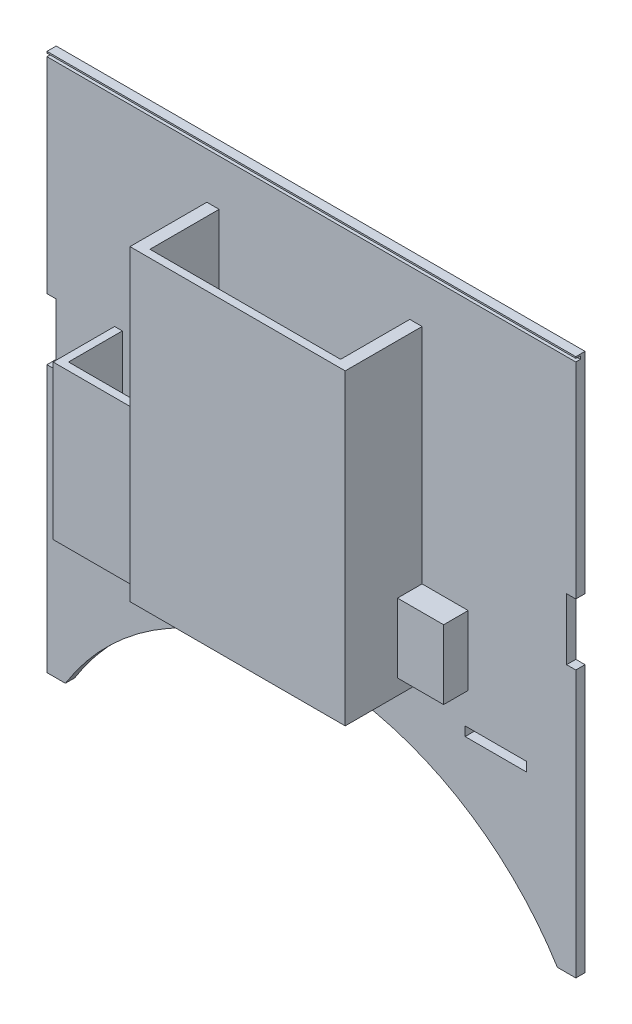
SolidWorks part; units mm, degrees
ref_plane "Plan de face" through (0, 0, 0) normal (0, 0, 1) x (1, 0, 0)
ref_plane "Plan de dessus" through (0, 0, 0) normal (0, 1, 0) x (1, 0, 0)
ref_plane "Plan de droite" through (0, 0, 0) normal (1, 0, 0) x (0, 0, -1)
sketch "Esquisse1" plane through (0, 0, 0) normal (0, 0, 1) x (1, 0, 0)
  line L0 (-109.4992, 0) -> (62.5008, 0)
  line L1 (62.5008, 0) -> (62.5008, -175)
  line L3 (-109.4992, -175) -> (-109.4992, 0)
  line L5 (-109.4992, -175) -> (-103.4992, -175)
  line L6 (56.5008, -175) -> (62.5008, -175)
  line L8 (-93.4992, -122) -> (-73.4992, -122)
  line L9 (-93.4992, -122) -> (-93.4992, -125)
  line L10 (-93.4992, -125) -> (-73.4992, -125)
  line L11 (-73.4992, -122) -> (-73.4992, -125)
  line L12 (-33.4992, -122) -> (-13.4992, -122)
  line L13 (-33.4992, -122) -> (-33.4992, -125)
  line L14 (-33.4992, -125) -> (-13.4992, -125)
  line L15 (-13.4992, -122) -> (-13.4992, -125)
  line L16 (26.5008, -122) -> (46.5008, -122)
  line L17 (26.5008, -122) -> (26.5008, -125)
  line L18 (26.5008, -125) -> (46.5008, -125)
  line L19 (46.5008, -122) -> (46.5008, -125)
  arc A0 (-103.4992, -175) -> (56.5008, -175) centre (-23.4992, -224.6279) cw
  point P12 (-106.4992, -175)
  dimension "D4" = 50
  dimension "D1" = 172
  dimension "D2" = 175
  dimension "D3" = 172
  dimension "D5" = 6
  dimension "D6" = 20
  dimension "D7" = 16
  dimension "D8" = 3
  dimension "D9" = 40
  dimension "D10" = 40
extrude "Boss.-Extru.1" add sketch "Esquisse1" along normal blind 3
sketch "Esquisse2" plane through (0, 0, 3) normal (0, 0, 1) x (1, 0, 0)
  line L20 (-109.4992, 0) -> (-109.4992, -1.5) construction
  line L21 (-109.4992, 0) -> (-109.4992, -175) construction
  line L22 (-109.4992, -1.5) -> (-109.4992, -0.5) construction
  line L23 (-109.4992, -1.5) -> (-109.4992, -0.5)
  line L24 (-109.4992, -1.5) -> (62.5008, -1.5)
  line L25 (-109.4992, -0.5) -> (62.5008, -0.5)
  line L26 (62.5008, -1.5) -> (62.5008, -0.5)
  line L27 (62.5008, -175) -> (62.5008, 0) construction
  line L28 (62.5008, 0) -> (-109.4992, 0) construction
  dimension "D1" = 0.5
  dimension "D2" = 1
extrude "Enlèv. mat.-Extru.1" cut sketch "Esquisse2" against normal blind 1.5
sketch "Esquisse4" plane through (0, 0, 3) normal (0, 0, 1) x (1, 0, 0)
  line L0 (-109.4992, -88.25) -> (-109.4992, -68.25) construction
  line L1 (-109.4992, -1.5) -> (-109.4992, -175) construction
  line L2 (-109.4992, -88.25) -> (-109.4992, -68.25)
  line L3 (-109.4992, -88.25) -> (-106.4992, -88.25)
  line L4 (-109.4992, -68.25) -> (-106.4992, -68.25)
  line L5 (-106.4992, -88.25) -> (-106.4992, -68.25)
  line L7 (62.5008, -88.25) -> (62.5008, -68.25)
  line L8 (62.5008, -175) -> (62.5008, -1.5) construction
  line L9 (62.5008, -88.25) -> (62.5008, -68.25) construction
  line L10 (62.5008, -88.25) -> (59.5008, -88.25)
  line L11 (62.5008, -68.25) -> (59.5008, -68.25)
  line L12 (59.5008, -88.25) -> (59.5008, -68.25)
  dimension "D1" = 3
  dimension "D2" = 20
extrude "Enlèv. mat.-Extru.2" cut sketch "Esquisse4" against normal through all
sketch "Esquisse5" plane through (0, 0, 3) normal (0, 0, 1) x (1, 0, 0)
  line L0 (-57.4992, -116.5) -> (12.5008, -116.5)
  line L1 (-57.4992, -116.5) -> (-57.4992, -16.5)
  line L2 (12.5008, -116.5) -> (12.5008, -16.5)
  line L3 (-57.4992, -16.5) -> (12.5008, -16.5)
  line L4 (-109.4992, -1.5) -> (-109.4992, -68.25) construction
  line L6 (-109.4992, -1.5) -> (62.5008, -1.5) construction
  dimension "D1" = 100
  dimension "D2" = 70
  dimension "D3" = 52
  dimension "D4" = 15
extrude "Boss.-Extru.2" add sketch "Esquisse5" along normal blind 25
sketch "Esquisse6" plane through (0, -16.5, 0) normal (0, 1, 0) x (1, 0, 0)
  line L0 (8.5008, -3) -> (8.5008, -25.5)
  line L1 (8.5008, -3) -> (-53.4992, -3)
  line L2 (8.5008, -25.5) -> (-53.4992, -25.5)
  line L3 (-53.4992, -3) -> (-53.4992, -25.5)
  line L4 (12.5008, -3) -> (-57.4992, -3) construction
  line L5 (12.5008, -28) -> (12.5008, -3) construction
  line L6 (-57.4992, -28) -> (-57.4992, -3) construction
  line L7 (12.5008, -28) -> (-57.4992, -28) construction
  dimension "D1" = 4
  dimension "D2" = 4
  dimension "D3" = 2.5
extrude "Enlèv. mat.-Extru.3" cut sketch "Esquisse6" against normal blind 95
sketch "Esquisse10" plane through (0, 0, 3) normal (0, 0, 1) x (1, 0, 0)
  line L0 (-57.4992, -116.5) -> (-87.4992, -116.5)
  line L1 (-57.4992, -116.5) -> (-57.4992, -66.5)
  line L2 (-87.4992, -116.5) -> (-87.4992, -66.5)
  line L3 (-57.4992, -66.5) -> (-87.4992, -66.5)
  dimension "D1" = 50
  dimension "D2" = 30
extrude "Boss.-Extru.3" add sketch "Esquisse10" along normal blind 20
sketch "Esquisse11" plane through (0, -66.5, 0) normal (0, 1, 0) x (1, 0, 0)
  line L0 (-59.9992, -3) -> (-59.9992, -20.5)
  line L1 (-59.9992, -3) -> (-84.9992, -3)
  line L2 (-59.9992, -20.5) -> (-84.9992, -20.5)
  line L3 (-84.9992, -3) -> (-84.9992, -20.5)
  line L4 (-57.4992, -3) -> (-87.4992, -3) construction
  line L5 (-57.4992, -23) -> (-57.4992, -3) construction
  dimension "D1" = 2.5
  dimension "D2" = 25
  dimension "D3" = 17.5
extrude "Enlèv. mat.-Extru.5" cut sketch "Esquisse11" against normal blind 47
sketch "Esquisse12" plane through (12.5008, 0, 0) normal (1, 0, 0) x (0, 0, -1)
  line L0 (-3, -111.5) -> (-3, -89)
  line L1 (-3, -111.5) -> (-11, -111.5)
  line L2 (-3, -89) -> (-11, -89)
  line L3 (-11, -111.5) -> (-11, -89)
  line L4 (-3, -116.5) -> (-3, -16.5) construction
  line L5 (-28, -116.5) -> (-3, -116.5) construction
  line L9 (-25.5, -111.5) -> (-3, -111.5) construction
  dimension "D1" = 22.5
  dimension "D2" = 8
extrude "Boss.-Extru.5" add sketch "Esquisse12" along normal blind 15
sketch "Esquisse15" plane through (8.5008, 0, 0) normal (-1, 0, 0) x (0, 0, 1)
  line L0 (3, -110.25) -> (10.5, -110.25)
  line L1 (3, -110.25) -> (3, -90.25)
  line L2 (10.5, -110.25) -> (10.5, -90.25)
  line L3 (3, -90.25) -> (10.5, -90.25)
  line L6 (3, -111.5) -> (3, -16.5) construction
  line L8 (25.5, -111.5) -> (3, -111.5) construction
  dimension "D1" = 20
  dimension "D2" = 7.5
  dimension "D3" = 1.25
extrude "Enlèv. mat.-Extru.7" cut sketch "Esquisse15" against normal blind 15
sketch "Esquisse17" plane through (0, 0, 0) normal (0, 0, -1) x (-1, 0, 0)
  line L0 (-23.5008, 0) -> (-23.5008, -92) construction
  line L1 (-62.5008, 0) -> (109.4992, 0) construction
  line L2 (-62.5008, -68.25) -> (-62.5008, 0) construction
  line L3 (-23.5008, -92) -> (-23.5008, -107)
  line L4 (-23.5008, -92) -> (-14.5008, -92)
  line L5 (-23.5008, -107) -> (-14.5008, -107)
  line L6 (-14.5008, -92) -> (-14.5008, -107)
  dimension "D1" = 39
  dimension "D2" = 92
  dimension "D3" = 9
  dimension "D4" = 15
extrude "Enlèv. mat.-Extru.8" cut sketch "Esquisse17" against normal up to next
sketch "Esquisse18" plane through (0, 0, 3) normal (0, 0, 1) x (1, 0, 0)
  arc A2 (-8.5555, -131.6784) -> (-36.7404, -131.4206) centre (-22.6479, -131.5495) ccw
  arc A3 (56.5008, -175) -> (-103.4992, -175) centre (-23.4992, -224.6279) ccw construction
  spline S0 degree 1 poles (-8.5555, -131.6784) (-36.7404, -131.4206) knots 0 0 1 1
extrude "Enlèv. mat.-Extru.9" cut sketch "Esquisse18" against normal blind 10
